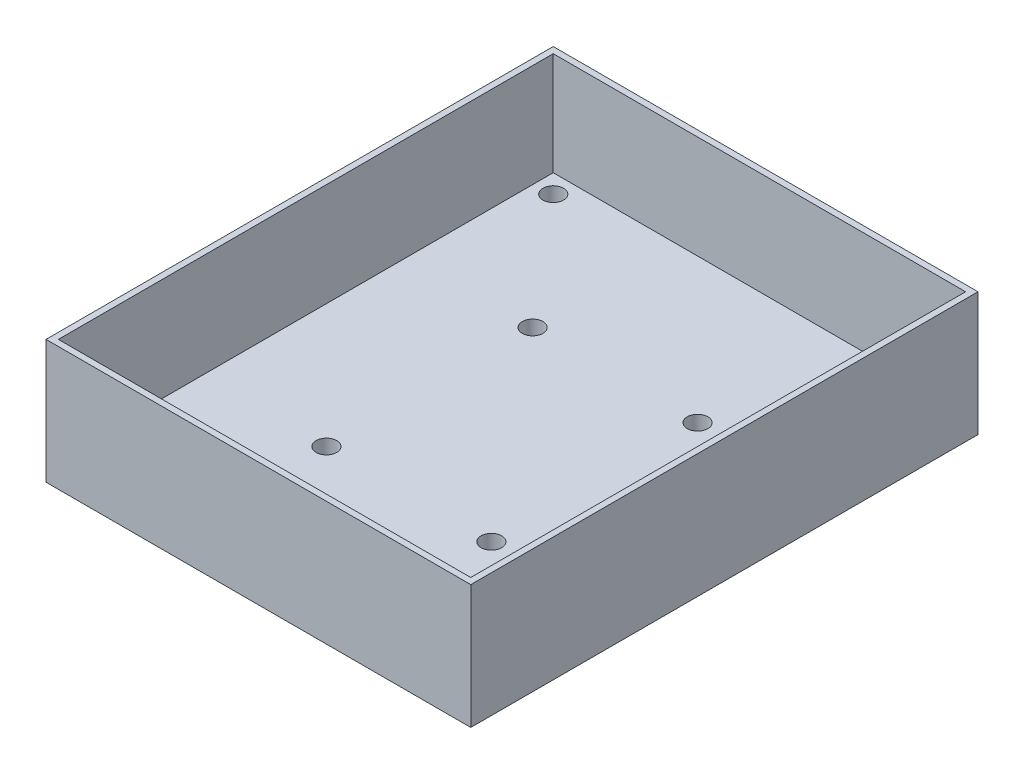
SolidWorks part; units mm, degrees
ref_plane "Front Plane" through (0, 0, 0) normal (0, 0, 1) x (1, 0, 0)
ref_plane "Top Plane" through (0, 0, 0) normal (0, 1, 0) x (1, 0, 0)
ref_plane "Right Plane" through (0, 0, 0) normal (1, 0, 0) x (0, 0, -1)
sketch "Sketch1" plane through (0, 0, 0) normal (0, 1, 0) x (1, 0, 0)
  line L1 (-103, 123) -> (103, 123)
  line L2 (-103, 123) -> (-103, -123)
  line L3 (-103, -123) -> (103, -123)
  line L4 (103, 123) -> (103, -123)
  line L5 (-103, 123) -> (103, -123) construction
  line L6 (-103, -123) -> (103, 123) construction
  point P0 (0, 0)
  dimension "D1" = 246
  dimension "D2" = 206
extrude "Boss-Extrude1" add sketch "Sketch1" along normal blind 60
sketch "Sketch2" plane through (0, 60, 0) normal (0, 1, 0) x (1, 0, 0)
  line L0 (103, 123) -> (-103, 123) construction
  line L1 (-100, 120) -> (100, 120)
  line L2 (-100, 120) -> (-100, -120)
  line L3 (-100, -120) -> (100, -120)
  line L4 (100, 120) -> (100, -120)
  line L5 (-100, 120) -> (100, -120) construction
  line L6 (-100, -120) -> (100, 120) construction
  line L7 (103, -123) -> (103, 123) construction
  point P0 (0, 0)
  dimension "D1" = 3
  dimension "D2" = 3
extrude "Cut-Extrude1" cut sketch "Sketch2" against normal blind 50
sketch "Sketch3" plane through (0, 0, 0) normal (0, -1, 0) x (1, 0, 0)
  line L0 (-103, 123) -> (103, 123) construction
  line L1 (-91, 111) -> (91, 111)
  line L2 (-91, 111) -> (-91, -111)
  line L3 (-91, -111) -> (91, -111)
  line L4 (91, 111) -> (91, -111)
  line L5 (-91, 111) -> (91, -111) construction
  line L6 (-91, -111) -> (91, 111) construction
  line L7 (103, 123) -> (103, -123) construction
  circle A0 centre (91, 111) radius 5
  circle A1 centre (91, -111) radius 5
  circle A2 centre (-91, -111) radius 5
  circle A3 centre (-91, 111) radius 5
  point P0 (0, 0)
  dimension "D3" = 10
  dimension "D1" = 12
  dimension "D2" = 12
extrude "Cut-Extrude3" cut sketch "Sketch3" against normal through all contours L2 A3 L1 | L1 A3 L2 | L4 A0 L1 | L1 A0 L4 | L3 A1 L4 | L4 A1 L3 | L2 A2 L3 | L3 A2 L2
sketch "Sketch4" plane through (0, 0, 0) normal (0, -1, 0) x (1, 0, 0)
  line L1 (-40, 50) -> (40, 50)
  line L2 (-40, 50) -> (-40, -50)
  line L3 (-40, -50) -> (40, -50)
  line L4 (40, 50) -> (40, -50)
  line L5 (-40, 50) -> (40, -50) construction
  line L6 (-40, -50) -> (40, 50) construction
  circle A0 centre (40, -50) radius 5
  circle A1 centre (-40, -50) radius 5
  circle A2 centre (-40, 50) radius 5
  circle A3 centre (40, 50) radius 5
  point P0 (0, 0)
  dimension "D3" = 10
  dimension "D1" = 100
  dimension "D2" = 80
extrude "Cut-Extrude4" cut sketch "Sketch4" against normal blind 10 contours A0 | A1 | A2 | A3
